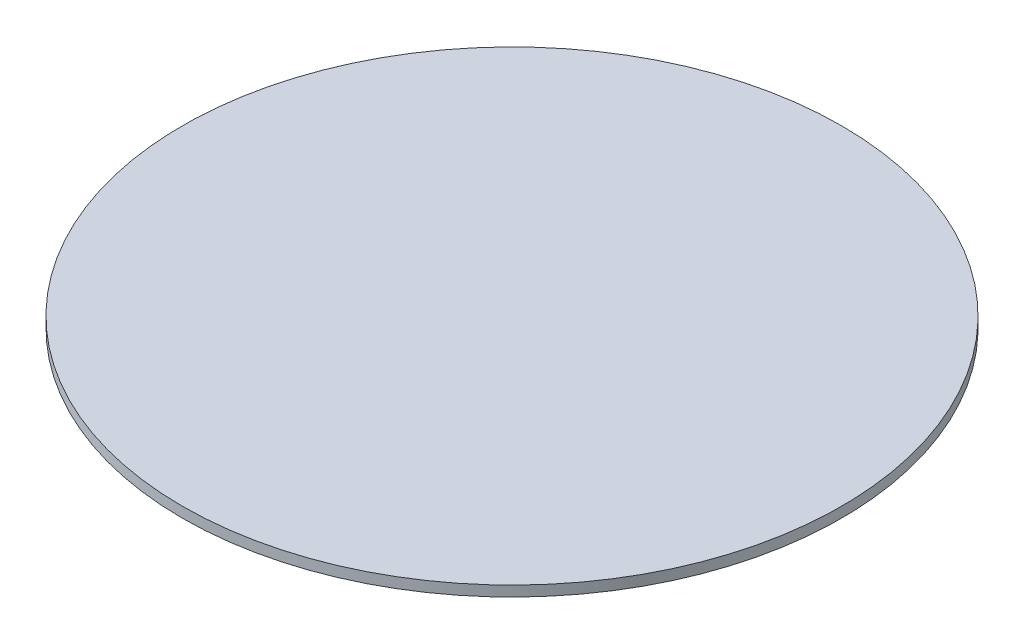
SolidWorks part; units mm, degrees
ref_plane "前视基准面" through (0, 0, 0) normal (0, 0, 1) x (1, 0, 0)
ref_plane "上视基准面" through (0, 0, 0) normal (0, 1, 0) x (1, 0, 0)
ref_plane "右视基准面" through (0, 0, 0) normal (1, 0, 0) x (0, 0, -1)
sketch "草图1" plane through (0, 0, 0) normal (0, 1, 0) x (1, 0, 0)
  circle A0 centre (0, 0) radius 193.5
  dimension "D1" = 387
extrude "凸台-拉伸1" add sketch "草图1" along normal blind 6.1
